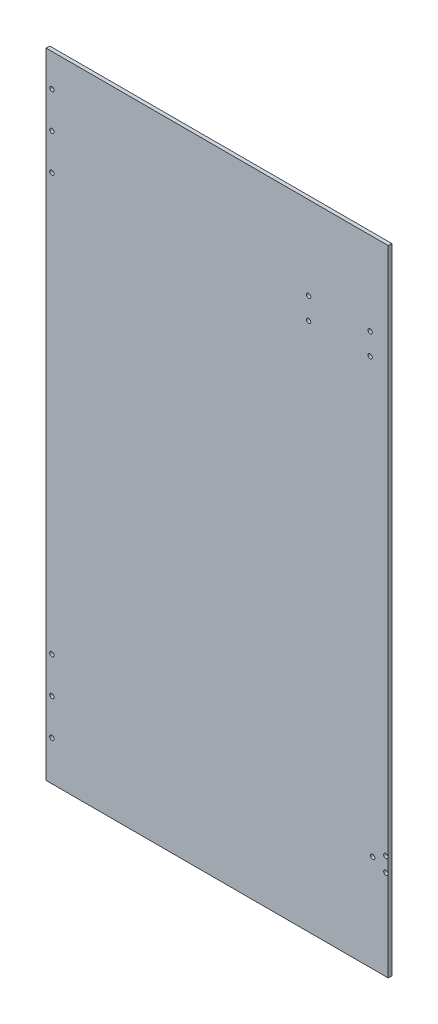
SolidWorks part; units mm, degrees
material "PE High Density"
ref_plane "Front Plane" through (0, 0, 0) normal (0, 0, 1) x (1, 0, 0)
ref_plane "Top Plane" through (0, 0, 0) normal (0, 1, 0) x (1, 0, 0)
ref_plane "Right Plane" through (0, 0, 0) normal (1, 0, 0) x (0, 0, -1)
sketch "Sketch1" plane through (0, 0, 0) normal (0, 0, 1) x (1, 0, 0)
  line L20 (0, 0) -> (600.075, 0)
  line L21 (0, 0) -> (0, -1112.52)
  line L22 (0, -1112.52) -> (600.075, -1112.52)
  line L23 (600.075, 0) -> (600.075, -1112.52)
  dimension "D1" = 600.075
  dimension "D2" = 1112.52
extrude "Boss-Extrude1" add sketch "Sketch1" along normal blind 6.35
sketch "Sketch2" plane through (0, 0, 0) normal (0, 0, -1) x (-1, 0, 0)
  line L0 (-600.075, -1112.52) -> (-600.075, 0) construction
  line L1 (-600.075, 0) -> (0, 0) construction
  line L2 (0, 0) -> (0, -1112.52) construction
  line L3 (0, -1112.52) -> (-600.075, -1112.52) construction
  circle A2 centre (-10.1092, -57.15) radius 3.81
  circle A3 centre (-10.1092, -120.65) radius 3.81
  circle A4 centre (-10.1092, -184.15) radius 3.81
  circle A5 centre (-10.1092, -915.67) radius 3.81
  circle A6 centre (-10.1092, -979.17) radius 3.81
  circle A7 centre (-10.1092, -1042.67) radius 3.81
  circle A8 centre (-595.8205, -929.289) radius 3.81
  circle A9 centre (-595.8205, -954.689) radius 3.81
  circle A10 centre (-572.8547, -941.989) radius 3.81
  circle A11 centre (-568.325, -146.05) radius 3.81
  circle A12 centre (-460.375, -146.05) radius 3.81
  circle A13 centre (-460.375, -184.15) radius 3.81
  circle A14 centre (-568.325, -184.15) radius 3.81
  point P34 (-572.8547, -738.789)
  dimension "D4" = 38.1
  dimension "D5" = 7.62
  dimension "D13" = 7.62
  dimension "D2" = 31.75
  dimension "D3" = 107.95
  dimension "D6" = 10.1092
  dimension "D7" = 57.15
  dimension "D8" = 63.5
  dimension "D9" = 63.5
  dimension "D10" = 69.85
  dimension "D11" = 63.5
  dimension "D12" = 63.5
  dimension "D14" = 22.9658
  dimension "D15" = 12.7
  dimension "D16" = 12.7
  dimension "D17" = 4.2545
  dimension "D18" = 157.831
  dimension "D19" = 146.05
extrude "Cut-Extrude1" cut sketch "Sketch2" against normal through all
